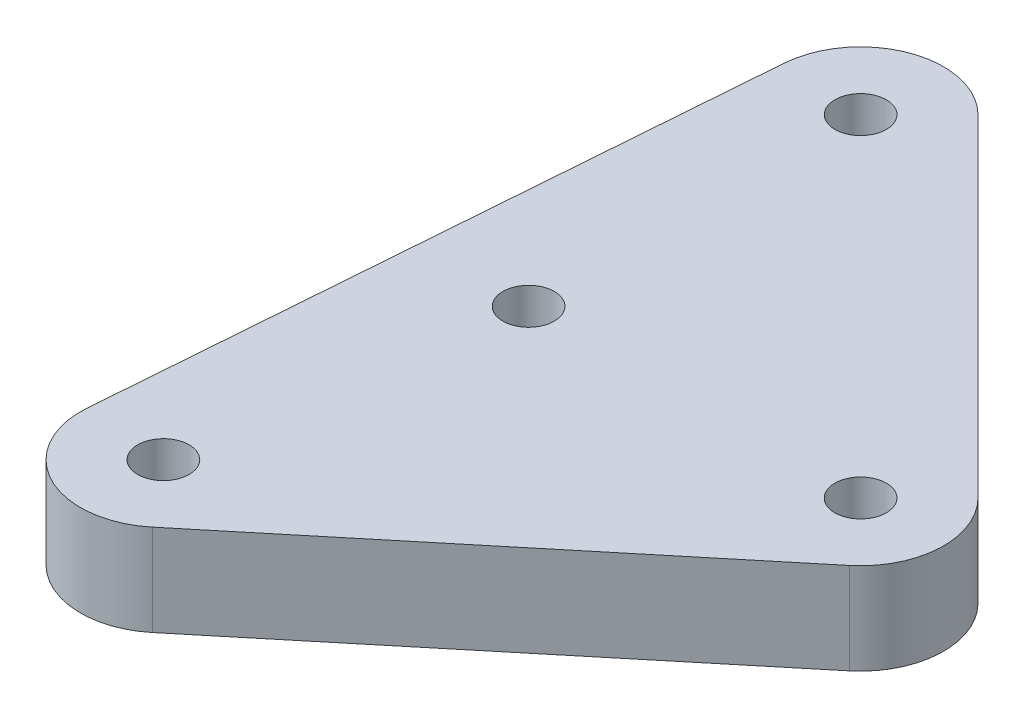
SolidWorks part; units mm, degrees
material "ﾎﾟﾘｵｷｼﾒﾁﾚﾝ(POM)ｱｾﾀｰﾙ共重合体"
ref_plane "正面" through (0, 0, 0) normal (0, 0, 1) x (1, 0, 0)
ref_plane "平面" through (0, 0, 0) normal (0, 1, 0) x (1, 0, 0)
ref_plane "右側面" through (0, 0, 0) normal (1, 0, 0) x (0, 0, -1)
sketch "ｽｹｯﾁ1" plane through (0, 0, 0) normal (0, 1, 0) x (1, 0, 0)
  line L0 (0, 20) -> (0, 0) construction
  line L1 (0, 0) -> (20, 0) construction
  line L2 (0, 0) -> (-3, -19) construction
  line L3 (-3, -19) -> (0, 20) construction
  line L4 (0, 20) -> (20, 0) construction
  line L5 (20, 0) -> (-3, -19) construction
  line L6 (-7.9853, -18.6165) -> (-4.9853, 20.3835)
  line L7 (3.5355, 23.5355) -> (23.5355, 3.5355)
  line L8 (23.1844, -3.8548) -> (0.1844, -22.8548)
  line L9 (-4.1515, 31.2226) -> (27.4238, -0.3527) construction
  line L10 (27.4238, -0.3527) -> (-8.8878, -30.3492) construction
  line L11 (-8.8878, -30.3492) -> (-4.1515, 31.2226) construction
  circle A0 centre (0, 20) radius 1.55
  circle A1 centre (0, 0) radius 1.55
  circle A2 centre (20, 0) radius 1.55
  circle A3 centre (-3, -19) radius 1.55
  arc A4 (23.5355, 3.5355) -> (23.1844, -3.8548) centre (20, 0) cw
  arc A5 (-4.9853, 20.3835) -> (3.5355, 23.5355) centre (0, 20) cw
  arc A6 (-7.9853, -18.6165) -> (0.1844, -22.8548) centre (-3, -19) ccw
  dimension "D1" = 3.1
  dimension "D2" = 20
  dimension "D3" = 19
  dimension "D4" = 3
  dimension "D5" = 5
extrude "ﾎﾞｽ - 押し出し1" add sketch "ｽｹｯﾁ1" along normal blind 5.5
